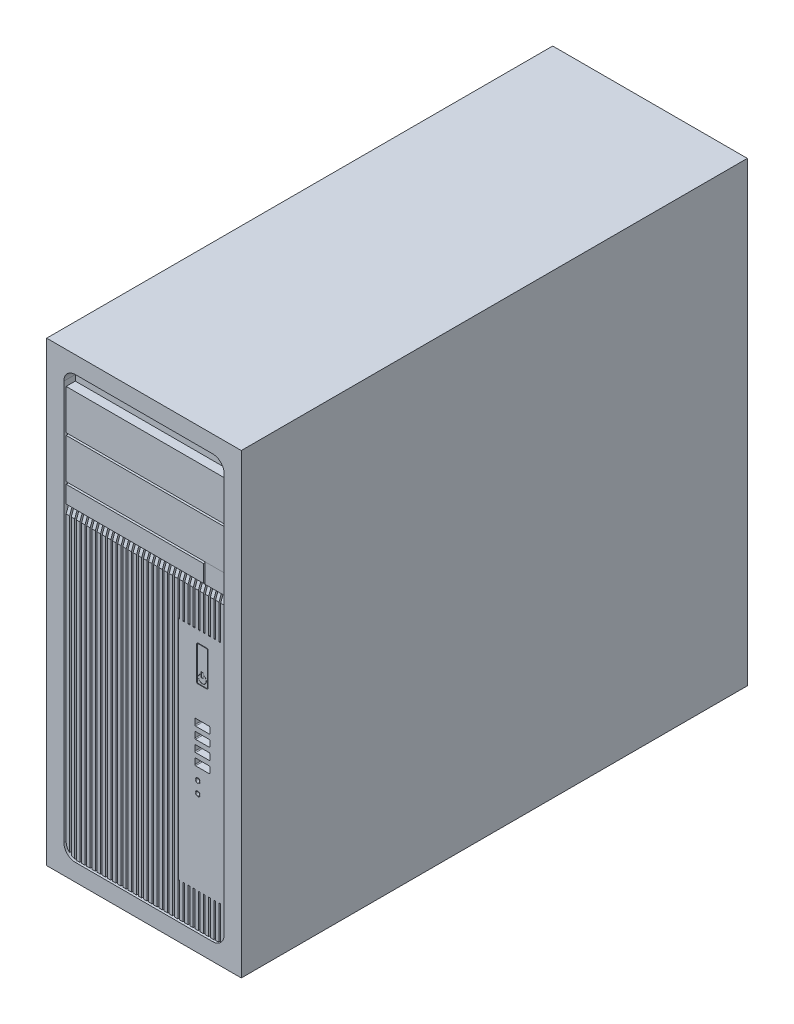
SolidWorks part; units mm, degrees
ref_plane "Front Plane" through (0, 0, 0) normal (0, 0, 1) x (1, 0, 0)
ref_plane "Top Plane" through (0, 0, 0) normal (0, 1, 0) x (1, 0, 0)
ref_plane "Right Plane" through (0, 0, 0) normal (1, 0, 0) x (0, 0, -1)
sketch "Sketch1" plane through (0, 0, 0) normal (0, 1, 0) x (1, 0, 0)
  line L1 (-85, -221) -> (85, -221)
  line L2 (-85, -221) -> (-85, 221)
  line L3 (-85, 221) -> (85, 221)
  line L4 (85, -221) -> (85, 221)
  line L5 (-85, -221) -> (85, 221) construction
  line L6 (-85, 221) -> (85, -221) construction
  point P0 (0, 0)
  dimension "D1" = 170
  dimension "D2" = 442
extrude "Boss-Extrude1" add sketch "Sketch1" along normal blind 399
sketch "Sketch2" plane through (0, 0, 221) normal (0, 0, 1) x (1, 0, 0)
  line L0 (-85, 399) -> (85, 399) construction
  line L1 (-60, 15) -> (60, 15)
  line L2 (-70, 25) -> (-70, 374)
  line L3 (-60, 384) -> (60, 384)
  line L4 (70, 25) -> (70, 374)
  line L5 (-70, 15) -> (70, 384) construction
  line L6 (-70, 384) -> (70, 15) construction
  line L7 (-85, 399) -> (-85, 0) construction
  line L8 (-85, 0) -> (85, 0) construction
  line L9 (85, 399) -> (85, 0) construction
  arc A0 (60, 15) -> (70, 25) centre (60, 25) ccw
  arc A1 (-60, 15) -> (-70, 25) centre (-60, 25) cw
  arc A2 (60, 384) -> (70, 374) centre (60, 374) cw
  arc A3 (-60, 384) -> (-70, 374) centre (-60, 374) ccw
  point P0 (0, 199.5)
  dimension "D5" = 10
  dimension "D1" = 15
  dimension "D2" = 15
  dimension "D3" = 15
  dimension "D4" = 15
extrude "Cut-Extrude1" cut sketch "Sketch2" against normal blind 10
sketch "Sketch3" plane through (0, 0, 211) normal (0, 0, 1) x (1, 0, 0)
  line L0 (70, 25) -> (70, 374) construction
  line L1 (-70, 334) -> (70, 334)
  line L2 (-70, 334) -> (-70, 369)
  line L3 (-70, 369) -> (70, 369)
  line L4 (70, 334) -> (70, 369)
  line L5 (-70, 334) -> (70, 369) construction
  line L6 (-70, 369) -> (70, 334) construction
  line L7 (60, 384) -> (-60, 384) construction
  line L8 (-70, 297) -> (70, 297)
  line L9 (-70, 297) -> (-70, 332)
  line L10 (-70, 332) -> (70, 332)
  line L11 (70, 297) -> (70, 332)
  line L12 (-70, 297) -> (70, 332) construction
  line L13 (-70, 332) -> (70, 297) construction
  point P0 (0, 351.5)
  point P7 (0, 314.5)
  dimension "D1" = 35
  dimension "D2" = 2
  dimension "D3" = 15
extrude "Boss-Extrude2" add sketch "Sketch3" along normal blind 8
sketch "Sketch4" plane through (0, 0, 211) normal (0, 0, 1) x (1, 0, 0)
  line L0 (-70, 374) -> (-70, 25) construction
  line L1 (50, 280) -> (-70, 280)
  line L2 (50, 280) -> (50, 295)
  line L3 (50, 295) -> (-70, 295)
  line L4 (-70, 280) -> (-70, 295)
  line L5 (50, 280) -> (-70, 295) construction
  line L6 (50, 295) -> (-70, 280) construction
  line L7 (-70, 297) -> (70, 297) construction
  line L8 (51.0938, 280) -> (70, 280)
  line L9 (51.0938, 280) -> (51.0938, 297)
  line L10 (51.0938, 297) -> (70, 297)
  line L11 (70, 280) -> (70, 297)
  line L12 (51.0938, 280) -> (70, 297) construction
  line L13 (51.0938, 297) -> (70, 280) construction
  point P0 (-10, 287.5)
  point P7 (60.5469, 288.5)
  dimension "D1" = 120
  dimension "D2" = 2
  dimension "D3" = 15
extrude "Boss-Extrude3" add sketch "Sketch4" along normal blind 8 separate body
sketch "Sketch5" plane through (0, 0, 211) normal (0, 0, 1) x (1, 0, 0)
  line L0 (-60, 15) -> (60, 15) construction
  line L1 (-70, 297) -> (-70, 25) construction
  line L3 (70, 25) -> (70, 297) construction
  line L4 (-60, 15) -> (60, 15)
  line L5 (-70, 278) -> (-70, 25)
  line L7 (70, 25) -> (70, 278)
  line L10 (-70, 278) -> (70, 278)
  arc A0 (-70, 25) -> (-60, 15) centre (-60, 25) ccw construction
  arc A1 (-70, 25) -> (-60, 15) centre (-60, 25) ccw
  arc A2 (60, 15) -> (70, 25) centre (60, 25) ccw construction
  arc A3 (60, 15) -> (70, 25) centre (60, 25) ccw
extrude "Boss-Extrude4" add sketch "Sketch5" along normal blind 8
chamfer "Chamfer1" distance 2 angle 70 1 edges at (0, 278, 219)
sketch "Sketch6" plane through (0, 0, 219) normal (0, 0, 1) x (1, 0, 0)
  line L0 (70, 278) -> (-70, 278) construction
  line L1 (-65.5, 278) -> (-67, 278)
  line L2 (-65.5, 278) -> (-65.5, 16.6484)
  line L3 (-70, 272.505) -> (-70, 278) construction
  line L4 (-67, 278) -> (-67, 17.8586)
  arc A0 (-70, 25) -> (-60, 15) centre (-60, 25) ccw construction
  arc A1 (-67, 17.8586) -> (-65.5, 16.6484) centre (-60, 25) ccw
  dimension "D1" = 3
  dimension "D2" = 1.5
extrude "Cut-Extrude2" cut sketch "Sketch6" against normal blind 8
sketch "Sketch7" plane through (0, 0, 219) normal (0, 0, 1) x (1, 0, 0)
  line L0 (-65.5, 278) -> (70, 278) construction
  line L1 (-62.5, 278) -> (-61, 278)
  line L2 (-62.5, 278) -> (-62.5, 15)
  line L3 (-62.5, 15) -> (-61, 15)
  line L4 (-61, 278) -> (-61, 15)
  line L5 (-60, 15) -> (60, 15) construction
  line L6 (-65.5, 272.505) -> (-65.5, 278) construction
  line L7 (-58, 278) -> (-58, 15)
  line L8 (-56.5, 278) -> (-56.5, 15)
  line L9 (-58, 278) -> (-56.5, 278)
  line L10 (-58, 15) -> (-56.5, 15)
  line L11 (-53.5, 278) -> (-53.5, 15)
  line L12 (-52, 278) -> (-52, 15)
  line L13 (-53.5, 278) -> (-52, 278)
  line L14 (-53.5, 15) -> (-52, 15)
  line L15 (-49, 278) -> (-49, 15)
  line L16 (-47.5, 278) -> (-47.5, 15)
  line L17 (-49, 278) -> (-47.5, 278)
  line L18 (-49, 15) -> (-47.5, 15)
  line L19 (-44.5, 278) -> (-44.5, 15)
  line L20 (-43, 278) -> (-43, 15)
  line L21 (-44.5, 278) -> (-43, 278)
  line L22 (-44.5, 15) -> (-43, 15)
  line L23 (-40, 278) -> (-40, 15)
  line L24 (-38.5, 278) -> (-38.5, 15)
  line L25 (-40, 278) -> (-38.5, 278)
  line L26 (-40, 15) -> (-38.5, 15)
  line L27 (-35.5, 278) -> (-35.5, 15)
  line L28 (-34, 278) -> (-34, 15)
  line L29 (-35.5, 278) -> (-34, 278)
  line L30 (-35.5, 15) -> (-34, 15)
  line L31 (-31, 278) -> (-31, 15)
  line L32 (-29.5, 278) -> (-29.5, 15)
  line L33 (-31, 278) -> (-29.5, 278)
  line L34 (-31, 15) -> (-29.5, 15)
  line L35 (-26.5, 278) -> (-26.5, 15)
  line L36 (-25, 278) -> (-25, 15)
  line L37 (-26.5, 278) -> (-25, 278)
  line L38 (-26.5, 15) -> (-25, 15)
  line L39 (-22, 278) -> (-22, 15)
  line L40 (-20.5, 278) -> (-20.5, 15)
  line L41 (-22, 278) -> (-20.5, 278)
  line L42 (-22, 15) -> (-20.5, 15)
  line L43 (-17.5, 278) -> (-17.5, 15)
  line L44 (-16, 278) -> (-16, 15)
  line L45 (-17.5, 278) -> (-16, 278)
  line L46 (-17.5, 15) -> (-16, 15)
  line L47 (-13, 278) -> (-13, 15)
  line L48 (-11.5, 278) -> (-11.5, 15)
  line L49 (-13, 278) -> (-11.5, 278)
  line L50 (-13, 15) -> (-11.5, 15)
  line L51 (-8.5, 278) -> (-8.5, 15)
  line L52 (-7, 278) -> (-7, 15)
  line L53 (-8.5, 278) -> (-7, 278)
  line L54 (-8.5, 15) -> (-7, 15)
  line L55 (-4, 278) -> (-4, 15)
  line L56 (-2.5, 278) -> (-2.5, 15)
  line L57 (-4, 278) -> (-2.5, 278)
  line L58 (-4, 15) -> (-2.5, 15)
  line L59 (0.5, 278) -> (0.5, 15)
  line L60 (2, 278) -> (2, 15)
  line L61 (0.5, 278) -> (2, 278)
  line L62 (0.5, 15) -> (2, 15)
  line L63 (5, 278) -> (5, 15)
  line L64 (6.5, 278) -> (6.5, 15)
  line L65 (5, 278) -> (6.5, 278)
  line L66 (5, 15) -> (6.5, 15)
  line L67 (9.5, 278) -> (9.5, 15)
  line L68 (11, 278) -> (11, 15)
  line L69 (9.5, 278) -> (11, 278)
  line L70 (9.5, 15) -> (11, 15)
  line L71 (14, 278) -> (14, 15)
  line L72 (15.5, 278) -> (15.5, 15)
  line L73 (14, 278) -> (15.5, 278)
  line L74 (14, 15) -> (15.5, 15)
  line L75 (18.5, 278) -> (18.5, 15)
  line L76 (20, 278) -> (20, 15)
  line L77 (18.5, 278) -> (20, 278)
  line L78 (18.5, 15) -> (20, 15)
  line L79 (23, 278) -> (23, 15)
  line L80 (24.5, 278) -> (24.5, 15)
  line L81 (23, 278) -> (24.5, 278)
  line L82 (23, 15) -> (24.5, 15)
  line L83 (27.5, 278) -> (27.5, 15)
  line L84 (29, 278) -> (29, 15)
  line L85 (27.5, 278) -> (29, 278)
  line L86 (27.5, 15) -> (29, 15)
  line L87 (32, 278) -> (32, 15)
  line L88 (33.5, 278) -> (33.5, 15)
  line L89 (32, 278) -> (33.5, 278)
  line L90 (32, 15) -> (33.5, 15)
  line L91 (36.5, 278) -> (36.5, 15)
  line L92 (38, 278) -> (38, 15)
  line L93 (36.5, 278) -> (38, 278)
  line L94 (36.5, 15) -> (38, 15)
  line L95 (41, 278) -> (41, 15)
  line L96 (42.5, 278) -> (42.5, 15)
  line L97 (41, 278) -> (42.5, 278)
  line L98 (41, 15) -> (42.5, 15)
  line L99 (45.5, 278) -> (45.5, 15)
  line L100 (47, 278) -> (47, 15)
  line L101 (45.5, 278) -> (47, 278)
  line L102 (45.5, 15) -> (47, 15)
  line L103 (50, 278) -> (50, 15)
  line L104 (51.5, 278) -> (51.5, 15)
  line L105 (50, 278) -> (51.5, 278)
  line L106 (50, 15) -> (51.5, 15)
  line L107 (54.5, 278) -> (54.5, 15)
  line L108 (56, 278) -> (56, 15)
  line L109 (54.5, 278) -> (56, 278)
  line L110 (54.5, 15) -> (56, 15)
  line L111 (59, 278) -> (59, 15)
  line L112 (60.5, 278) -> (60.5, 15)
  line L113 (59, 278) -> (60.5, 278)
  line L114 (59, 15) -> (60.5, 15)
  line L115 (63.5, 278) -> (63.5, 15)
  line L116 (65, 278) -> (65, 15)
  line L117 (63.5, 278) -> (65, 278)
  line L118 (63.5, 15) -> (65, 15)
  line L119 (68, 278) -> (68, 15)
  line L120 (69.5, 278) -> (69.5, 15)
  line L121 (68, 278) -> (69.5, 278)
  line L122 (68, 15) -> (69.5, 15)
  dimension "D1" = 3
  dimension "D2" = 1.5
  dimension "D3" = 30
extrude "Cut-Extrude3" cut sketch "Sketch7" against normal blind 8
sketch "Sketch8" plane through (0, 0, 219) normal (0, 0, 1) x (1, 0, 0)
  line L0 (60, 15) -> (70, 15)
  line L1 (70, 15) -> (70, 25)
  line L3 (63.5, 15.6325) -> (63.5, 272.505)
  line L4 (63.5, 272.505) -> (60.5, 272.505)
  line L5 (60.5, 272.505) -> (60.5, 15.0125)
  line L6 (63.5, 15.6325) -> (63.5, 272.505)
  line L7 (63.5, 272.505) -> (60.5, 272.505)
  line L8 (60.5, 272.505) -> (60.5, 15.0125)
  arc A0 (60, 15) -> (70, 25) centre (60, 25) ccw construction
  arc A1 (60.5, 15.0125) -> (63.5, 15.6325) centre (60, 25) ccw
  arc A2 (60.5, 15.0125) -> (63.5, 15.6325) centre (60, 25) ccw
  arc A3 (60, 15) -> (70, 25) centre (60, 25) ccw
  arc M8 (60.5, 15.0125) -> (63.5, 15.6325) centre (60, 25) ccw
  dimension "D1" = 0
extrude "Boss-Extrude5" add sketch "Sketch8" against normal blind 8 contours A3 L0 L1 M8
sketch "Sketch9" plane through (0, 0, 219) normal (0, 0, 1) x (1, 0, 0)
  line L1 (70, 25) -> (70, 374) construction
  line L2 (70, 242.505) -> (28, 242.505)
  line L3 (70, 242.505) -> (70, 45)
  line L4 (70, 45) -> (28, 45)
  line L6 (28, 242.505) -> (28, 45)
  line L7 (50, 272.505) -> (47, 272.505) construction
  line L8 (38, 15) -> (41, 15) construction
  point P6 (48.5, 272.505)
  dimension "D1" = 42
  dimension "D2" = 30
  dimension "D3" = 30
extrude "Boss-Extrude6" add sketch "Sketch9" against normal blind 8
sketch "Sketch10" plane through (0, 0, 219) normal (0, 0, 1) x (1, 0, 0)
  line L0 (28, 217.005) -> (70, 217.005) construction
  line L1 (28, 242.505) -> (28, 45) construction
  line L2 (70, 25) -> (70, 272.505) construction
  line L3 (47, 242.505) -> (45.5, 242.505) construction
  line L4 (45.0572, 201.505) -> (52.9428, 201.505)
  line L5 (44.0572, 202.505) -> (44.0572, 231.505)
  line L6 (45.0572, 232.505) -> (52.9428, 232.505)
  line L7 (53.9428, 202.505) -> (53.9428, 231.505)
  line L8 (44.0572, 201.505) -> (53.9428, 232.505) construction
  line L9 (44.0572, 232.505) -> (53.9428, 201.505) construction
  line L10 (45.5572, 202.005) -> (52.4428, 202.005)
  line L11 (44.5572, 203.005) -> (44.5572, 231.005)
  line L12 (45.5572, 232.005) -> (52.4428, 232.005)
  line L13 (53.4428, 203.005) -> (53.4428, 231.005)
  line L14 (44.5572, 202.005) -> (53.4428, 232.005) construction
  line L15 (44.5572, 232.005) -> (53.4428, 202.005) construction
  arc A0 (44.0572, 202.505) -> (45.0572, 201.505) centre (45.0572, 202.505) ccw
  arc A1 (45.5572, 202.005) -> (44.5572, 203.005) centre (45.5572, 203.005) cw
  arc A2 (52.4428, 202.005) -> (53.4428, 203.005) centre (52.4428, 203.005) ccw
  arc A3 (52.9428, 201.505) -> (53.9428, 202.505) centre (52.9428, 202.505) ccw
  arc A4 (52.9428, 232.505) -> (53.9428, 231.505) centre (52.9428, 231.505) cw
  arc A5 (52.4428, 232.005) -> (53.4428, 231.005) centre (52.4428, 231.005) cw
  arc A6 (44.5572, 231.005) -> (45.5572, 232.005) centre (45.5572, 231.005) cw
  arc A7 (44.0572, 231.505) -> (45.0572, 232.505) centre (45.0572, 231.505) cw
  point P6 (49, 217.005)
  point P11 (49, 217.005)
  point P16 (46.25, 242.505)
  dimension "D5" = 1
  dimension "D1" = 0.5
  dimension "D2" = 0.5
  dimension "D3" = 30
  dimension "D4" = 10
extrude "Cut-Extrude4" cut sketch "Sketch10" against normal blind 8
sketch "Sketch11" plane through (0, 0, 219) normal (0, 0, 1) x (1, 0, 0)
  line L0 (44.5572, 207.005) -> (53.4428, 207.005)
  line L1 (53.4428, 203.005) -> (53.4428, 231.005) construction
  line L2 (44.5572, 231.005) -> (44.5572, 203.005) construction
  line L4 (48, 207.805) -> (50, 207.805)
  line L5 (48, 207.805) -> (48, 212.205)
  line L6 (48, 212.205) -> (50, 212.205)
  line L7 (50, 207.805) -> (50, 212.205)
  line L8 (48, 207.805) -> (50, 212.205) construction
  line L9 (48, 212.205) -> (50, 207.805) construction
  line L10 (48.2, 208.005) -> (49.8, 208.005)
  line L11 (48.2, 208.005) -> (48.2, 212.005)
  line L12 (48.2, 212.005) -> (49.8, 212.005)
  line L13 (49.8, 208.005) -> (49.8, 212.005)
  line L14 (48.2, 208.005) -> (49.8, 212.005) construction
  line L15 (48.2, 212.005) -> (49.8, 208.005) construction
  line L16 (48, 212.205) -> (48.2, 212.205)
  line L17 (48, 212.205) -> (48, 212.005)
  line L18 (48, 212.005) -> (48.2, 212.005)
  line L19 (48.2, 212.205) -> (48.2, 212.005)
  line L21 (47.4672, 210.1516) -> (47.4672, 209.9275)
  line L22 (49, 210.005) -> (49, 209.2855) construction
  line L23 (50.5328, 210.1516) -> (50.5328, 209.9275)
  line L24 (45.5572, 202.005) -> (52.4428, 202.005) construction
  arc A0 (47.4672, 210.1516) -> (50.5328, 210.1516) centre (49, 207.005) ccw
  arc A1 (47.4672, 209.9275) -> (50.5328, 209.9275) centre (49, 207.005) ccw
  arc A4 (48.7712, 210.5771) -> (48.7409, 210.5751) centre (49, 207.005) ccw
  arc A5 (48.8519, 210.3752) -> (48.8322, 210.3743) centre (49, 207.005) ccw
  arc A6 (49.1678, 210.3743) -> (49.1481, 210.3752) centre (49, 207.005) ccw
  arc A7 (49.2591, 210.5751) -> (49.2288, 210.5771) centre (49, 207.005) ccw
  point P5 (49, 207.005)
  point P10 (49, 210.005)
  point P15 (49, 210.005)
  dimension "D1" = 0.2
  dimension "D4" = 7
  dimension "D2" = 0.2
  dimension "D3" = 4
  dimension "D5" = 3
  dimension "D6" = 5
  dimension "D7" = 2
extrude "Cut-Extrude5" cut sketch "Sketch11" against normal blind 1 contours L6 L19 L12 L13 L10 L11 L18 L5 L4 L7 | A1 L0 A0 L23 | L19 L6 L5 L18 | A1 L21 A0 L0 | A1 L0 A0
sketch "Sketch13" plane through (0, 0, 219) normal (0, 0, 1) x (1, 0, 0)
  line L1 (43.11, 168.545) -> (54.89, 168.545)
  line L2 (42.35, 169.305) -> (42.35, 173.705)
  line L3 (43.11, 174.465) -> (54.89, 174.465)
  line L4 (55.65, 169.305) -> (55.65, 173.705)
  line L5 (42.35, 168.545) -> (55.65, 174.465) construction
  line L6 (42.35, 174.465) -> (55.65, 168.545) construction
  line L8 (49, 171.505) -> (28, 171.505) construction
  line L9 (28, 242.505) -> (28, 45) construction
  line L10 (49, 171.505) -> (70, 171.505) construction
  line L11 (70, 25) -> (70, 272.505) construction
  line L12 (42.35, 158.545) -> (42.35, 164.465)
  line L13 (42.35, 164.465) -> (55.65, 164.465)
  line L14 (42.35, 158.545) -> (55.65, 158.545)
  line L15 (55.65, 158.545) -> (55.65, 164.465)
  line L16 (42.35, 148.545) -> (42.35, 154.465)
  line L17 (42.35, 154.465) -> (55.65, 154.465)
  line L18 (42.35, 148.545) -> (55.65, 148.545)
  line L19 (55.65, 148.545) -> (55.65, 154.465)
  line L20 (42.35, 138.545) -> (42.35, 144.465)
  line L21 (42.35, 144.465) -> (55.65, 144.465)
  line L22 (42.35, 138.545) -> (55.65, 138.545)
  line L23 (55.65, 138.545) -> (55.65, 144.465)
  line L24 (45.0572, 201.505) -> (52.9428, 201.505) construction
  arc A0 (54.89, 174.465) -> (55.65, 173.705) centre (54.89, 173.705) cw
  arc A1 (54.89, 168.545) -> (55.65, 169.305) centre (54.89, 169.305) ccw
  arc A2 (43.11, 168.545) -> (42.35, 169.305) centre (43.11, 169.305) cw
  arc A3 (42.35, 173.705) -> (43.11, 174.465) centre (43.11, 173.705) cw
  arc A4 (43.11, 158.545) -> (42.35, 159.305) centre (43.11, 159.305) cw
  arc A5 (42.35, 163.705) -> (43.11, 164.465) centre (43.11, 163.705) cw
  arc A6 (54.89, 164.465) -> (55.65, 163.705) centre (54.89, 163.705) cw
  arc A7 (54.89, 158.545) -> (55.65, 159.305) centre (54.89, 159.305) ccw
  arc A8 (43.11, 148.545) -> (42.35, 149.305) centre (43.11, 149.305) cw
  arc A9 (42.35, 153.705) -> (43.11, 154.465) centre (43.11, 153.705) cw
  arc A10 (54.89, 154.465) -> (55.65, 153.705) centre (54.89, 153.705) cw
  arc A11 (54.89, 148.545) -> (55.65, 149.305) centre (54.89, 149.305) ccw
  arc A12 (43.11, 138.545) -> (42.35, 139.305) centre (43.11, 139.305) cw
  arc A13 (42.35, 143.705) -> (43.11, 144.465) centre (43.11, 143.705) cw
  arc A14 (54.89, 144.465) -> (55.65, 143.705) centre (54.89, 143.705) cw
  arc A15 (54.89, 138.545) -> (55.65, 139.305) centre (54.89, 139.305) ccw
  point P0 (49, 171.505)
  dimension "D5" = 0.76
  dimension "D1" = 13.3
  dimension "D2" = 5.92
  dimension "D4" = 30
  dimension "D3" = 4
  dimension "D6" = 4
extrude "Cut-Extrude6" cut sketch "Sketch13" against normal blind 8 contours L14 A7 L15 A6 L13 A5 L12 A4 | A3 L2 A2 L1 A1 L4 A0 L3 | L18 A11 L19 A10 L17 A9 L16 A8 | L22 A15 L23 A14 L21 A13 L20 A12
sketch "Sketch14" plane through (0, 0, 219) normal (0, 0, 1) x (1, 0, 0)
  circle A0 centre (44.9801, 128.3306) radius 1.9
  circle A1 centre (44.9801, 118.3306) radius 1.9
  circle A2 centre (44.9801, 128.3306) radius 2.1
  circle A3 centre (44.9801, 118.3306) radius 2.1
  circle A4 centre (44.9801, 128.3306) radius 1.7
  circle A5 centre (44.9801, 118.3306) radius 1.7
  dimension "D1" = 3.8
  dimension "D2" = 10
  dimension "D3" = 0.2
  dimension "D4" = 0.2
  dimension "D5" = 0.2
extrude "Cut-Extrude7" cut sketch "Sketch14" against normal blind 8 contours A2 A0 | A4 | A5 | A3 A1
